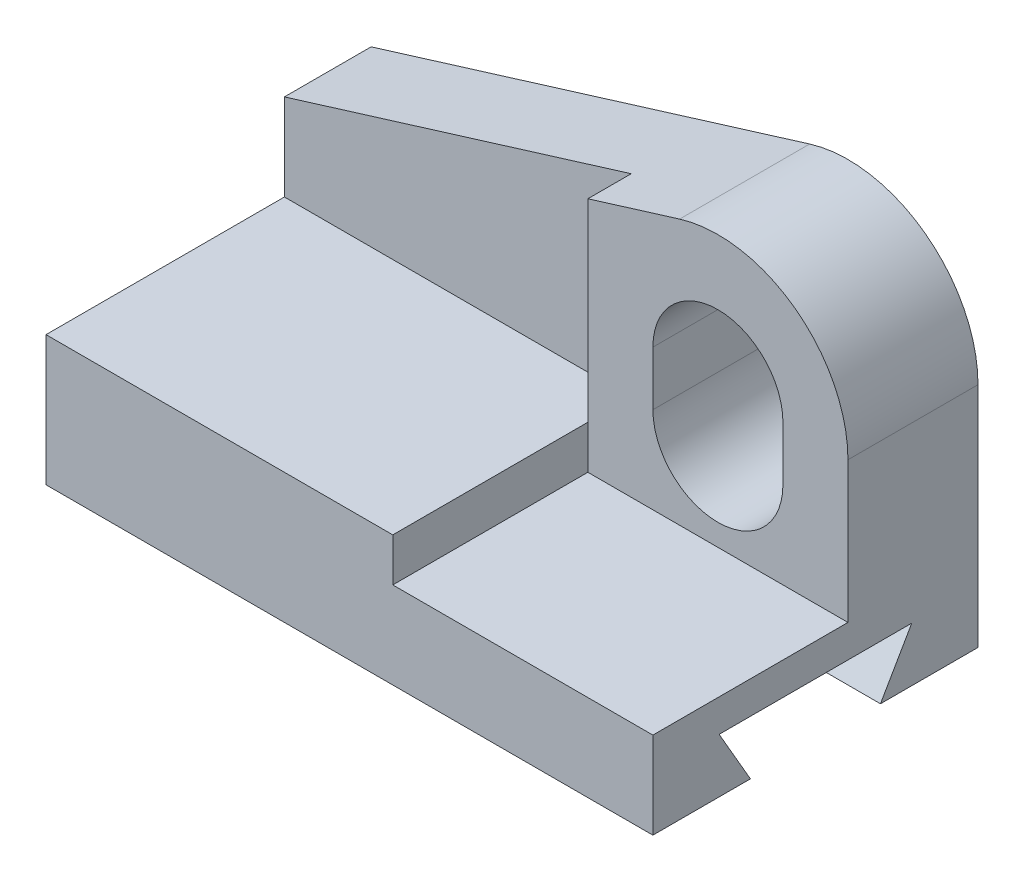
SolidWorks part; units mm, degrees
ref_plane "前视基准面" through (0, 0, 0) normal (0, 0, 1) x (1, 0, 0)
ref_plane "上视基准面" through (0, 0, 0) normal (0, 1, 0) x (1, 0, 0)
ref_plane "右视基准面" through (0, 0, 0) normal (1, 0, 0) x (0, 0, -1)
other "Configuration Table"
sketch "草图1" plane through (0, 0, 0) normal (0, 1, 0) x (1, 0, 0)
  line L1 (-28, -15) -> (28, -15)
  line L2 (-28, -15) -> (-28, 15)
  line L3 (-28, 15) -> (28, 15)
  line L4 (28, -15) -> (28, 15)
  line L5 (-28, -15) -> (28, 15) construction
  line L6 (-28, 15) -> (28, -15) construction
  point P0 (0, 0)
  dimension "D1" = 56
  dimension "D2" = 30
extrude "凸台-拉伸1" add sketch "草图1" along normal blind 12
sketch "草图2" plane through (-28, 0, 0) normal (-1, 0, 0) x (0, 0, 1)
  line L0 (0, 0) -> (0, 8.3128) construction
  line L1 (-15, 0) -> (15, 0) construction
  line L2 (-6, 0) -> (-8.8868, 5)
  line L3 (-8.8868, 5) -> (8.8868, 5)
  line L4 (8.8868, 5) -> (6, 0)
  line L5 (-6, 0) -> (6, 0)
  dimension "D1" = 12
  dimension "D2" = 5
  dimension "D3" = 60
extrude "切除-拉伸1" cut sketch "草图2" against normal through all
sketch "草图3" plane through (0, 0, 15) normal (0, 0, 1) x (1, 0, 0)
  line L0 (28, 12) -> (28, 8)
  line L1 (28, 12) -> (28, 0) construction
  line L2 (28, 8) -> (4, 8)
  line L3 (4, 8) -> (4, 12)
  line L4 (-28, 12) -> (28, 12) construction
  line L5 (4, 12) -> (28, 12)
  dimension "D1" = 4
  dimension "D2" = 24
extrude "切除-拉伸2" cut sketch "草图3" against normal through all
sketch "草图4" plane through (0, 0, -15) normal (0, 0, -1) x (-1, 0, 0)
  line L0 (-16, 8) -> (-16, 23.4868) construction
  line L2 (-4, 12) -> (-4, 8) construction
  line L3 (-16, 16) -> (-16, 21) construction
  line L4 (-22, 16) -> (-22, 21)
  line L5 (-10, 16) -> (-10, 21)
  line L6 (-4, 8) -> (-28, 8) construction
  line L7 (-16, 21) -> (-1.044, 21) construction
  line L8 (-4, 21) -> (-4, 8)
  line L9 (-4, 8) -> (-28, 8)
  line L10 (-28, 8) -> (-28, 21)
  line L11 (28, 12) -> (28, 20)
  line L12 (28, 20) -> (-12.4666, 32.468)
  line L13 (-28, 0) -> (28, 0) construction
  line L14 (28, 12) -> (-4, 12)
  arc A0 (-22, 16) -> (-10, 16) centre (-16, 16) ccw
  arc A1 (-10, 21) -> (-22, 21) centre (-16, 21) ccw
  arc A2 (-4, 21) -> (-28, 21) centre (-16, 21) ccw
  point P6 (-16, 18.5)
  line M12 (-4, 12) -> (-4, 8)
  line M13 (-4, 8) -> (-28, 8)
  line M17 (28, 12) -> (-4, 12)
  dimension "D2" = 6
  dimension "D5" = 12
  dimension "D1" = 12
  dimension "D3" = 8
  dimension "D4" = 5
  dimension "D6" = 20
extrude "凸台-拉伸2" add sketch "草图4" against normal blind 8 contours A2 L8 L11 L12 M17 | L8 A2 L10 A1 L5 A0 L4 M13 M12
sketch "草图5" plane through (0, 0, -7) normal (0, 0, 1) x (1, 0, 0)
  line L0 (10, 16) -> (10, 21) construction
  line L1 (22, 16) -> (22, 21) construction
  line L2 (28, 21) -> (28, 0) construction
  line L3 (28, 21) -> (28, 0)
  line L4 (22, 16) -> (22, 21)
  line L5 (10, 16) -> (10, 21)
  line L6 (12.4666, 32.468) -> (-28, 20)
  line L7 (-28, 20) -> (-28, 12)
  line L8 (-28, 12) -> (4, 12)
  line L9 (4, 12) -> (4, 8)
  line L10 (4, 8) -> (28, 8)
  line L11 (28, 8) -> (28, 21)
  line L12 (12.4666, 32.468) -> (-28, 20)
  line L13 (-28, 20) -> (-28, 12)
  line L14 (-28, 12) -> (4, 12)
  line L15 (4, 12) -> (4, 8)
  line L16 (4, 8) -> (28, 8)
  line L17 (28, 8) -> (28, 21)
  line L18 (4, 12) -> (4, 29.8594)
  arc A0 (22, 21) -> (10, 21) centre (16, 21) ccw construction
  arc A1 (28, 21) -> (12.4666, 32.468) centre (16, 21) ccw
  arc A2 (28, 21) -> (12.4666, 32.468) centre (16, 21) ccw
  arc A3 (10, 16) -> (22, 16) centre (16, 16) ccw construction
  arc A4 (28, 21) -> (12.4666, 32.468) centre (16, 21) ccw construction
  arc A5 (28, 21) -> (12.4666, 32.468) centre (16, 21) ccw
  arc A6 (10, 16) -> (22, 16) centre (16, 16) ccw
  arc A7 (22, 21) -> (10, 21) centre (16, 21) ccw
  line M12 (12.4666, 32.468) -> (-28, 20)
  line M15 (4, 12) -> (4, 8)
  line M16 (4, 8) -> (28, 8)
  line M17 (28, 8) -> (28, 21)
  arc M18 (28, 21) -> (12.4666, 32.468) centre (16, 21) ccw
  arc M19 (10, 21) -> (22, 21) centre (16, 21) cw
  line M20 (22, 21) -> (22, 16)
  arc M21 (22, 16) -> (10, 16) centre (16, 16) cw
  line M22 (10, 16) -> (10, 21)
  dimension "D1" = 0
extrude "凸台-拉伸3" add sketch "草图5" along normal blind 4 contours L18 M15 M16 M17 M18 M12 M22 M19 M20 M21
